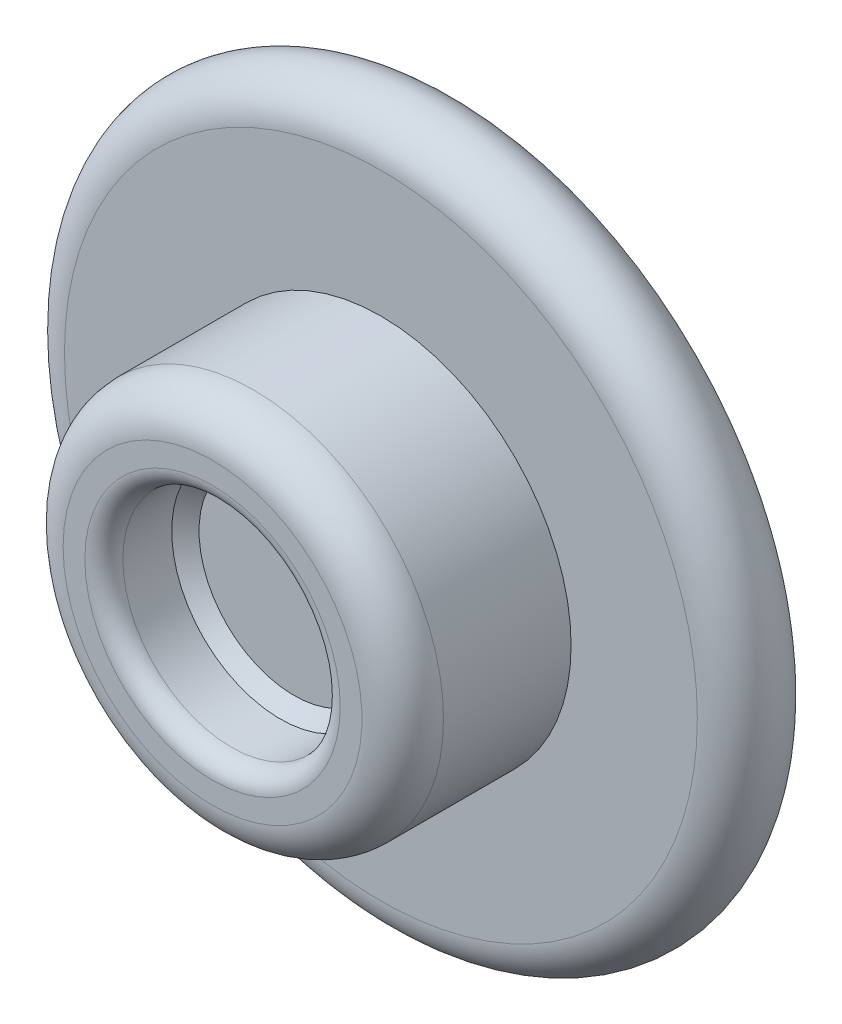
SolidWorks part; units mm, degrees
ref_plane "Alzado" through (0, 0, 0) normal (0, 0, 1) x (1, 0, 0)
ref_plane "Planta" through (0, 0, 0) normal (0, 1, 0) x (1, 0, 0)
ref_plane "Vista lateral" through (0, 0, 0) normal (1, 0, 0) x (0, 0, -1)
sketch "Croquis1" plane through (0, 0, 0) normal (1, 0, 0) x (0, 0, -1)
  line L0 (-43.4213, 0) -> (43.4213, 0) construction
  line L2 (0, -38.4861) -> (0, 38.4861) construction
  line L3 (0, 15.5462) -> (3, 15.5462) construction
  line L4 (0, 35.5462) -> (4, 35.5462) construction
  line L5 (4, 35.5462) -> (4, 18) construction
  line L6 (4, 18) -> (14.1961, 18) construction
  line L7 (14.1961, 18) -> (14.1961, 7) construction
  line L8 (3, 11) -> (9, 11) construction
  line L9 (10.5, 9.5) -> (10.5, 4) construction
  line L10 (10.5, 4) -> (12.998, 4)
  line L12 (12.998, 4) -> (13.5, 3.498)
  line L13 (13.5, 3.498) -> (13.5, 0)
  line L25 (3, 15.5462) -> (3, 11) construction
  line L26 (0, 15.5462) -> (0, 35.5462) construction
  line L27 (13.5, 0) -> (25.5, 0) construction
  line L29 (10.5, 9.5) -> (10.5, 8) construction
  line L31 (10.5, 8) -> (12, 8) construction
  line L32 (12, 8) -> (14.1961, 18) construction
  line L33 (10.5, 7) -> (10.5, 4)
  line L34 (10.5, 7) -> (16.6961, 7)
  line L37 (13.5, 0) -> (25.5, 0)
  line L38 (16.6961, 7) -> (16.6961, 17)
  line L39 (16.6961, 17) -> (24.1899, 4.676)
  arc A0 (24.1899, 4.676) -> (25.5, 0) centre (16.5, 0) cw
  arc A1 (9, 11) -> (10.5, 9.5) centre (9, 9.5) cw construction
  point P3 (0, 0)
  point P6 (0, 0)
  point P28 (13.5, 0)
  point P32 (3, 13.2731)
  dimension "D5" = 4
  dimension "D11" = 9
  dimension "D4" = 18
  dimension "D2" = 11
  dimension "D3" = 20
  dimension "D6" = 4
  dimension "D7" = 10.1961
  dimension "D8" = 11
  dimension "D9" = 3
  dimension "D10" = 2.5
  dimension "D12" = 7.5
  dimension "D13" = 6
  dimension "D14" = 13.5
  dimension "D15" = 45
  dimension "D16" = 8
  dimension "D17" = 0.71
  dimension "D18" = 1.5
  dimension "D19" = 35.5462
  dimension "D20" = 3
  dimension "D21" = 3
  dimension "D22" = 1
  dimension "D23" = 31.303
revolve "Revolución1" add sketch "Croquis1" angle 360 about L0
fillet "Redondeo3" radius 0.7 1 edges at (4, 0, -10.5)
fillet "Redondeo5" radius 1.5 2 edges at (7, 0, -10.5) (17, 0, -16.6961)
ref_plane "Plano1" through (0, 0, -25.5) normal (0, 0, -1) x (-1, 0, 0)
sketch "Croquis2" plane through (0, 0, -25.5) normal (0, 0, -1) x (-1, 0, 0)
  line L0 (4.676, 0) -> (-4.676, 0) construction
  line L5 (-0.35, 2.6772) -> (0.5573, 4.1148)
  line L8 (0.5573, 4.1148) -> (-0.216, 3.6772)
  line L9 (-0.216, 3.6772) -> (1.0137, 5.2072)
  line L10 (1.0137, 5.2072) -> (0.4203, 4.2671)
  line L11 (0.4203, 4.2671) -> (0.85, 4.5102)
  line L12 (0.85, 4.5102) -> (0.35, 2.6772)
  line L13 (4.5102, -0.85) -> (2.6772, -0.35)
  line L26 (2.6772, 0.35) -> (4.1148, -0.5573)
  line L27 (4.1148, -0.5573) -> (3.6772, 0.216)
  line L28 (3.6772, 0.216) -> (5.2072, -1.0137)
  line L29 (5.2072, -1.0137) -> (4.2671, -0.4203)
  line L30 (4.2671, -0.4203) -> (4.5102, -0.85)
  line L31 (-0.85, -4.5102) -> (-0.35, -2.6772)
  line L32 (0.35, -2.6772) -> (-0.5573, -4.1148)
  line L33 (-0.5573, -4.1148) -> (0.216, -3.6772)
  line L34 (0.216, -3.6772) -> (-1.0137, -5.2072)
  line L35 (-1.0137, -5.2072) -> (-0.4203, -4.2671)
  line L36 (-0.4203, -4.2671) -> (-0.85, -4.5102)
  line L37 (-4.5102, 0.85) -> (-2.6772, 0.35)
  line L38 (-2.6772, -0.35) -> (-4.1148, 0.5573)
  line L39 (-4.1148, 0.5573) -> (-3.6772, -0.216)
  line L40 (-3.6772, -0.216) -> (-5.2072, 1.0137)
  line L41 (-5.2072, 1.0137) -> (-4.2671, 0.4203)
  line L42 (-4.2671, 0.4203) -> (-4.5102, 0.85)
  circle A0 centre (0, 0) radius 4.676 construction
  circle A3 centre (0, 0) radius 1.5
  circle A4 centre (0, 0) radius 2.5
  arc A5 (0.35, 2.6772) -> (-0.35, 2.6772) centre (0, 0) ccw
  circle A6 centre (0, 0) radius 2.7 construction
  arc A8 (2.6772, -0.35) -> (2.6772, 0.35) centre (0, 0) ccw
  arc A9 (-0.35, -2.6772) -> (0.35, -2.6772) centre (0, 0) ccw
  arc A10 (-2.6772, 0.35) -> (-2.6772, -0.35) centre (0, 0) ccw
  point P1 (0, 2.7)
  point P6 (0, 0)
  point P16 (0, 0)
  point P44 (0, 0)
  dimension "D2" = 3
  dimension "D3" = 1
  dimension "D5" = 0.2
  dimension "D6" = 1.9
  dimension "D7" = 1.7
  dimension "D8" = 0.7
  dimension "D9" = 0.5
  dimension "D10" = 1
  dimension "D11" = 2.53
  dimension "D12" = 0.566
  dimension "D14" = 0.6637
  dimension "D4" = 0.2
  dimension "D13" = 4
extrude "Cortar-Extruir1" cut sketch "Croquis2" against normal blind 3
ref_plane "Plano2" through (0, 0, -23.77) normal (0, 0, 1) x (1, 0, 0)
sketch "Croquis3" plane through (0, 0, -23.77) normal (0, 0, 1) x (1, 0, 0)
  line L0 (12.4254, 0) -> (-12.4254, 0) construction
  line L1 (-0.35, 6.6668) -> (0.5573, 8.1044)
  line L2 (0.5573, 8.1044) -> (-0.216, 7.6668)
  line L3 (-0.216, 7.6668) -> (1.0137, 9.1968)
  line L4 (1.0137, 9.1968) -> (0.4203, 8.2567)
  line L5 (0.4203, 8.2567) -> (0.85, 8.4999)
  line L6 (0.85, 8.4999) -> (0.35, 6.6668)
  line L7 (3.6355, 5.5993) -> (5.2146, 6.229)
  line L8 (5.2146, 6.229) -> (4.3317, 6.3296)
  line L9 (4.3317, 6.3296) -> (6.2258, 6.8446)
  line L10 (6.2258, 6.8446) -> (5.1932, 6.4328)
  line L11 (5.1932, 6.4328) -> (5.6838, 6.3769)
  line L12 (5.6838, 6.3769) -> (4.2018, 5.1879)
  line L13 (6.2324, 2.393) -> (7.88, 1.9744)
  line L20 (7.88, 1.9744) -> (7.2248, 2.5746)
  line L21 (7.2248, 2.5746) -> (9.0599, 1.8779)
  line L22 (9.0599, 1.8779) -> (7.9825, 2.1517)
  line L23 (7.9825, 2.1517) -> (8.3465, 1.8182)
  line L24 (8.3465, 1.8182) -> (6.4487, 1.7273)
  line L25 (6.4487, -1.7273) -> (7.5356, -3.0345)
  line L26 (7.5356, -3.0345) -> (7.3583, -2.1637)
  line L27 (7.3583, -2.1637) -> (8.4335, -3.806)
  line L28 (8.4335, -3.806) -> (7.7227, -2.9512)
  line L29 (7.7227, -2.9512) -> (7.8212, -3.435)
  line L30 (7.8212, -3.435) -> (6.2324, -2.393)
  line L31 (4.2018, -5.1879) -> (4.3128, -6.8842)
  line L32 (4.3128, -6.8842) -> (4.6812, -6.0756)
  line L33 (4.6812, -6.0756) -> (4.5857, -8.0362)
  line L34 (4.5857, -8.0362) -> (4.5131, -6.9269)
  line L35 (4.5131, -6.9269) -> (4.3084, -7.3761)
  line L36 (4.3084, -7.3761) -> (3.6355, -5.5993)
  line L37 (0.35, -6.6668) -> (-0.5573, -8.1044)
  line L38 (-0.5573, -8.1044) -> (0.216, -7.6668)
  line L39 (0.216, -7.6668) -> (-1.0137, -9.1968)
  line L40 (-1.0137, -9.1968) -> (-0.4203, -8.2567)
  line L41 (-0.4203, -8.2567) -> (-0.85, -8.4999)
  line L42 (-0.85, -8.4999) -> (-0.35, -6.6668)
  line L43 (-3.6355, -5.5993) -> (-5.2146, -6.229)
  line L44 (-5.2146, -6.229) -> (-4.3317, -6.3296)
  line L45 (-4.3317, -6.3296) -> (-6.2258, -6.8446)
  line L46 (-6.2258, -6.8446) -> (-5.1932, -6.4328)
  line L47 (-5.1932, -6.4328) -> (-5.6838, -6.3769)
  line L48 (-5.6838, -6.3769) -> (-4.2018, -5.1879)
  line L49 (-6.2324, -2.393) -> (-7.88, -1.9744)
  line L50 (-7.88, -1.9744) -> (-7.2248, -2.5746)
  line L51 (-7.2248, -2.5746) -> (-9.0599, -1.8779)
  line L52 (-9.0599, -1.8779) -> (-7.9825, -2.1517)
  line L53 (-7.9825, -2.1517) -> (-8.3465, -1.8182)
  line L54 (-8.3465, -1.8182) -> (-6.4487, -1.7273)
  line L55 (-6.4487, 1.7273) -> (-7.5356, 3.0345)
  line L56 (-7.5356, 3.0345) -> (-7.3583, 2.1637)
  line L57 (-7.3583, 2.1637) -> (-8.4335, 3.806)
  line L58 (-8.4335, 3.806) -> (-7.7227, 2.9512)
  line L59 (-7.7227, 2.9512) -> (-7.8212, 3.435)
  line L60 (-7.8212, 3.435) -> (-6.2324, 2.393)
  line L61 (-4.2018, 5.1879) -> (-4.3128, 6.8842)
  line L62 (-4.3128, 6.8842) -> (-4.6812, 6.0756)
  line L63 (-4.6812, 6.0756) -> (-4.5857, 8.0362)
  line L64 (-4.5857, 8.0362) -> (-4.5131, 6.9269)
  line L65 (-4.5131, 6.9269) -> (-4.3084, 7.3761)
  line L66 (-4.3084, 7.3761) -> (-3.6355, 5.5993)
  circle A0 centre (0, 0) radius 1.5 construction
  circle A1 centre (0, 0) radius 4.676 construction
  arc A2 (0.35, 6.6668) -> (-0.35, 6.6668) centre (0, 0) ccw
  circle A4 centre (0, 0) radius 4.676 construction
  circle A5 centre (0, 0) radius 12.4254 construction
  arc A6 (4.2018, 5.1879) -> (3.6355, 5.5993) centre (0, 0) ccw
  arc A7 (6.4487, 1.7273) -> (6.2324, 2.393) centre (0, 0) ccw
  arc A8 (6.2324, -2.393) -> (6.4487, -1.7273) centre (0, 0) ccw
  arc A9 (3.6355, -5.5993) -> (4.2018, -5.1879) centre (0, 0) ccw
  arc A10 (-0.35, -6.6668) -> (0.35, -6.6668) centre (0, 0) ccw
  arc A11 (-4.2018, -5.1879) -> (-3.6355, -5.5993) centre (0, 0) ccw
  arc A12 (-6.4487, -1.7273) -> (-6.2324, -2.393) centre (0, 0) ccw
  arc A13 (-6.2324, 2.393) -> (-6.4487, 1.7273) centre (0, 0) ccw
  arc A14 (-3.6355, 5.5993) -> (-4.2018, 5.1879) centre (0, 0) ccw
  point P1 (0, 4.676)
  point P5 (0, 0)
  point P14 (0, 0)
  point P39 (0, 6.676)
  point P88 (0, 0)
  dimension "D1" = 3
  dimension "D2" = 17
  dimension "D3" = 0.2
  dimension "D4" = 1.9
  dimension "D5" = 1.7
  dimension "D6" = 0.7
  dimension "D7" = 0.5
  dimension "D8" = 1
  dimension "D9" = 2.53
  dimension "D10" = 1.3637
  dimension "D11" = 2
  dimension "D12" = 10
extrude "Cortar-Extruir3" cut sketch "Croquis3" along normal blind 3
